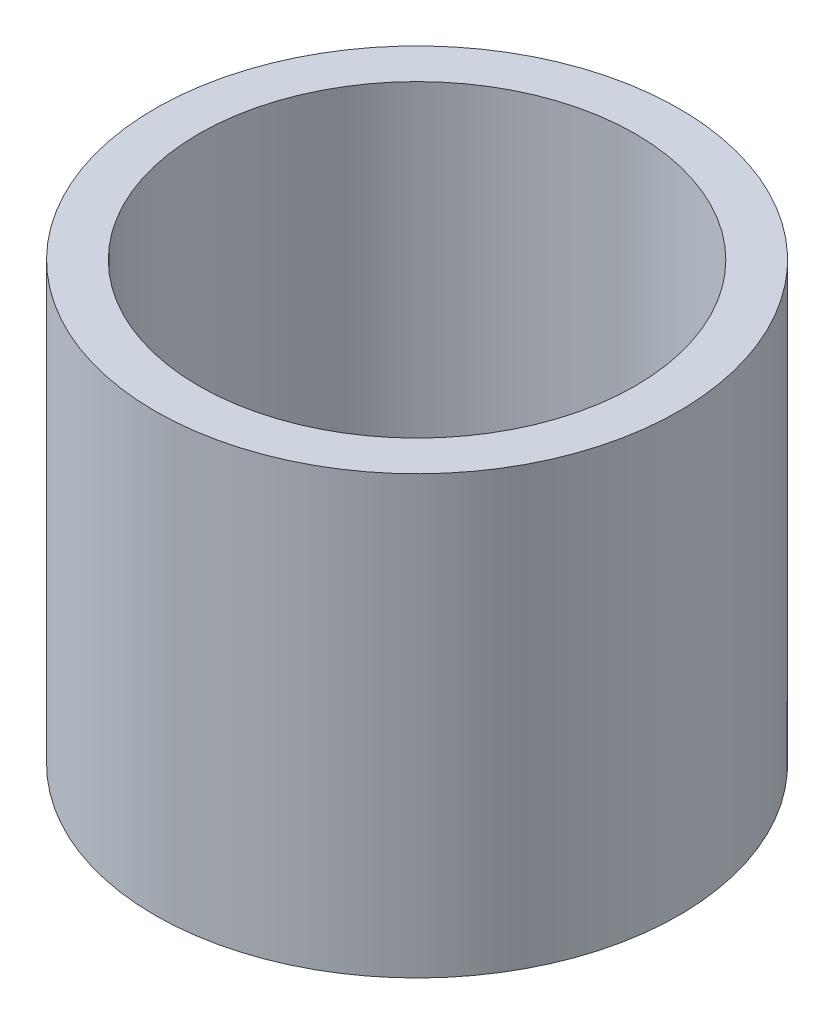
SolidWorks part; units mm, degrees
ref_plane "Front Plane" through (0, 0, 0) normal (0, 0, 1) x (1, 0, 0)
ref_plane "Top Plane" through (0, 0, 0) normal (0, 1, 0) x (1, 0, 0)
ref_plane "Right Plane" through (0, 0, 0) normal (1, 0, 0) x (0, 0, -1)
sketch "Sketch1" plane through (0, 0, 0) normal (0, 1, 0) x (1, 0, 0)
  circle A0 centre (0, 0) radius 25
  circle A1 centre (0, 0) radius 30
  dimension "D1" = 50
  dimension "D2" = 5
extrude "Boss-Extrude1" add sketch "Sketch1" along normal mid plane 50
sketch "Sketch3" plane through (0, -25, 0) normal (0, -1, 0) x (1, 0, 0)
  circle A0 centre (0, 0) radius 25 construction
  circle A3 centre (0, 0) radius 25
extrude "Boss-Extrude2" add sketch "Sketch3" against normal blind 10
sketch "Sketch5" plane through (0, 25, 0) normal (0, 1, 0) x (1, 0, 0)
  point P0 (0, 0)
